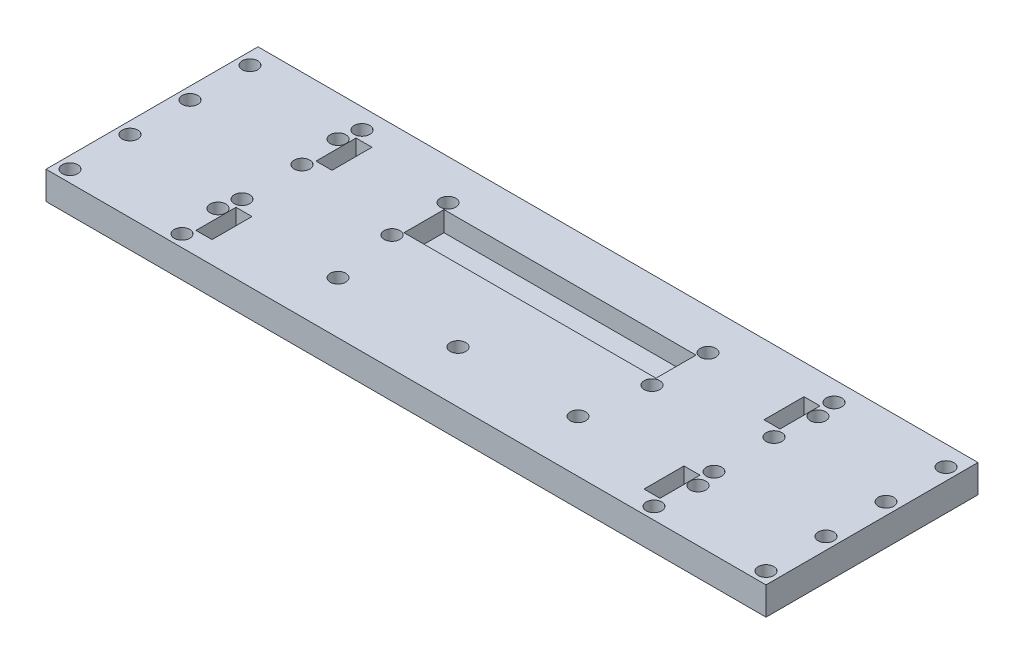
SolidWorks part; units mm, degrees
ref_plane "前视基准面" through (0, 0, 0) normal (0, 0, 1) x (1, 0, 0)
ref_plane "上视基准面" through (0, 0, 0) normal (0, 1, 0) x (1, 0, 0)
ref_plane "右视基准面" through (0, 0, 0) normal (1, 0, 0) x (0, 0, -1)
other "Configuration Table"
sketch "草图1" plane through (0, 0, 0) normal (0, 1, 0) x (1, 0, 0)
  line L0 (0, 20) -> (150, 20)
  line L1 (0, 0) -> (150, 0)
  line L2 (0, 0) -> (0, 30)
  line L3 (0, 30) -> (150, 30)
  line L4 (150, 0) -> (150, 30)
  line L6 (0, 30) -> (25, 30)
  line L7 (0, 30) -> (0, 60)
  line L8 (0, 60) -> (25, 60)
  line L9 (25, 30) -> (25, 60)
  line L10 (150, 30) -> (125, 30)
  line L11 (150, 30) -> (150, 60)
  line L12 (150, 60) -> (125, 60)
  line L13 (125, 30) -> (125, 60)
  line L14 (0, 0) -> (-15, 0)
  line L15 (0, 0) -> (0, 60)
  line L16 (0, 60) -> (-15, 60)
  line L17 (-15, 0) -> (-15, 60)
  line L18 (150, 60) -> (165, 60)
  line L19 (150, 60) -> (150, 0)
  line L20 (150, 0) -> (165, 0)
  line L21 (165, 60) -> (165, 0)
  circle A1 centre (15, 20) radius 1.95
  circle A2 centre (45, 20) radius 1.95
  circle A3 centre (75, 20) radius 1.95
  circle A4 centre (105, 20) radius 1.95
  circle A5 centre (135, 20) radius 1.95
  circle A6 centre (15, 50) radius 1.95
  circle A7 centre (135, 50) radius 1.95
  dimension "D5" = 15
  dimension "D6" = 30
  dimension "D7" = 3.9
  dimension "D12" = 3.9
  dimension "D14" = 15
  dimension "D15" = 15
  dimension "D16" = 3.9
  dimension "D17" = 30
  dimension "D1" = 30
  dimension "D2" = 150
  dimension "D3" = 10
  dimension "D8" = 40
  dimension "D9" = 25
  dimension "D10" = 25
  dimension "D11" = 30
  dimension "D13" = 30
  dimension "D18" = 15
  dimension "D19" = 15
  dimension "D4" = 5
extrude "凸台-拉伸1" add sketch "草图1" along normal blind 7 contours L3 L9 L8 L7 A6 | A5 L0 A4 A3 A2 A1 L2 L1 L4 | A5 L0 L4 L3 L2 A1 A2 A3 A4 | L13 L3 L11 L12 A7 | L15 L14 L17 L16 | L19 L18 L21 L20
sketch "草图2" plane through (0, 7, 0) normal (0, 1, 0) x (1, 0, 0)
  line L0 (-15, 0) -> (-15, 60) construction
  line L1 (-12, 55) -> (16, 55)
  line L2 (-12, 55) -> (-12, 40)
  line L3 (-12, 40) -> (16, 40)
  line L4 (16, 55) -> (16, 40)
  line L5 (-15, 60) -> (25, 60) construction
  line L6 (-12, 25) -> (-12, 10)
  line L7 (-12, 25) -> (16, 25)
  line L8 (16, 25) -> (16, 10)
  line L9 (-12, 10) -> (16, 10)
  line L10 (75, 0) -> (75, 91.2711)
  line L11 (-15, 0) -> (165, 0) construction
  line L12 (-12, 47.5) -> (19, 47.5)
  line L13 (-15, 32.5) -> (25, 32.5)
  line L14 (17, 42.5) -> (21, 42.5)
  line L15 (17, 42.5) -> (17, 52.5)
  line L16 (17, 52.5) -> (21, 52.5)
  line L17 (21, 42.5) -> (21, 52.5)
  line L18 (19, 52.5) -> (19, 42.5) construction
  line L19 (17, 47.5) -> (21, 47.5) construction
  line L20 (25, 30) -> (25, 60) construction
  line L21 (17, 12.5) -> (21, 12.5)
  line L22 (17, 22.5) -> (17, 12.5)
  line L23 (17, 22.5) -> (21, 22.5)
  line L24 (21, 22.5) -> (21, 12.5)
  line L25 (133, 22.5) -> (133, 12.5)
  line L26 (133, 22.5) -> (129, 22.5)
  line L27 (129, 22.5) -> (129, 12.5)
  line L28 (133, 12.5) -> (129, 12.5)
  line L29 (133, 42.5) -> (129, 42.5)
  line L30 (133, 42.5) -> (133, 52.5)
  line L31 (133, 52.5) -> (129, 52.5)
  line L32 (129, 42.5) -> (129, 52.5)
  circle A0 centre (-12, 55) radius 1.95
  circle A1 centre (16, 55) radius 1.95
  circle A2 centre (16, 40) radius 1.95
  circle A3 centre (16, 25) radius 1.95
  circle A4 centre (-12, 25) radius 1.95
  circle A5 centre (-12, 10) radius 1.95
  circle A6 centre (16, 10) radius 1.95
  circle A7 centre (-12, 40) radius 1.95
  circle A8 centre (162, 10) radius 1.95
  circle A9 centre (134, 10) radius 1.95
  circle A10 centre (134, 25) radius 1.95
  circle A11 centre (162, 25) radius 1.95
  circle A12 centre (134, 40) radius 1.95
  circle A13 centre (162, 40) radius 1.95
  circle A14 centre (134, 55) radius 1.95
  circle A15 centre (162, 55) radius 1.95
  point P49 (2, 40)
  dimension "D7" = 3.9
  dimension "D8" = 3.9
  dimension "D9" = 3.9
  dimension "D10" = 3.9
  dimension "D11" = 3.9
  dimension "D12" = 3.9
  dimension "D13" = 3.9
  dimension "D14" = 3.9
  dimension "D1" = 15
  dimension "D2" = 28
  dimension "D3" = 3
  dimension "D4" = 5
  dimension "D6" = 30
  dimension "D15" = 4
  dimension "D16" = 10
  dimension "D17" = 1
  dimension "D18" = 7.5
  dimension "D5" = 2
extrude "切除-拉伸1" cut sketch "草图2" against normal blind 6 contours L1 A0 L2 | L2 A0 L1 | L2 A7 L3 | L3 A7 L2 | L4 A2 L3 | L3 A2 L4 | L4 A1 L1 | L1 A1 L4 | L6 A5 L9 | L9 A5 L6 | L7 A4 L6 | L6 A4 L7 | L8 A3 L7 | L7 A3 L8 | L8 A6 L9 | L9 A6 L8 | A9 | A8 | A11 | A10 | A12 | A14 | A15 | A13
sketch "草图4" plane through (0, 7, 0) normal (0, 1, 0) x (1, 0, 0)
  line L0 (75, 0) -> (75, 91.2711) construction
  line L1 (-15, 32.5) -> (25, 32.5) construction
  line L2 (-12, 47.5) -> (19, 47.5) construction
  line L3 (75, 0) -> (75, 91.2711)
  line L4 (-12, 25) -> (-12, 10)
  line L5 (-12, 10) -> (16, 10)
  line L6 (16, 10) -> (16, 25)
  line L7 (16, 25) -> (-12, 25)
  line L8 (-12, 25) -> (-12, 10)
  line L9 (-12, 10) -> (16, 10)
  line L10 (16, 10) -> (16, 25)
  line L11 (16, 25) -> (-12, 25)
  line L12 (16, 55) -> (-12, 55)
  line L13 (16, 40) -> (16, 55)
  line L14 (-12, 40) -> (16, 40)
  line L15 (-12, 55) -> (-12, 40)
  line L16 (16, 55) -> (-12, 55)
  line L17 (16, 40) -> (16, 55)
  line L18 (-12, 40) -> (16, 40)
  line L19 (-12, 55) -> (-12, 40)
  line L20 (129, 42.5) -> (133, 42.5)
  line L21 (129, 52.5) -> (129, 42.5)
  line L22 (133, 52.5) -> (129, 52.5)
  line L23 (133, 42.5) -> (133, 52.5)
  line L24 (129, 42.5) -> (133, 42.5)
  line L25 (129, 52.5) -> (129, 42.5)
  line L26 (133, 52.5) -> (129, 52.5)
  line L27 (133, 42.5) -> (133, 52.5)
  line L28 (133, 12.5) -> (133, 22.5)
  line L29 (129, 12.5) -> (133, 12.5)
  line L30 (129, 22.5) -> (129, 12.5)
  line L31 (133, 22.5) -> (129, 22.5)
  line L32 (133, 12.5) -> (133, 22.5)
  line L33 (129, 12.5) -> (133, 12.5)
  line L34 (129, 22.5) -> (129, 12.5)
  line L35 (133, 22.5) -> (129, 22.5)
  line L36 (17, 12.5) -> (21, 12.5)
  line L37 (21, 12.5) -> (21, 22.5)
  line L38 (21, 22.5) -> (17, 22.5)
  line L39 (17, 22.5) -> (17, 12.5)
  line L40 (17, 12.5) -> (21, 12.5)
  line L41 (21, 12.5) -> (21, 22.5)
  line L42 (21, 22.5) -> (17, 22.5)
  line L43 (17, 22.5) -> (17, 12.5)
  line L44 (17, 42.5) -> (21, 42.5)
  line L45 (17, 52.5) -> (17, 42.5)
  line L46 (21, 52.5) -> (17, 52.5)
  line L47 (21, 42.5) -> (21, 52.5)
  line L48 (17, 42.5) -> (21, 42.5)
  line L49 (17, 52.5) -> (17, 42.5)
  line L50 (21, 52.5) -> (17, 52.5)
  line L51 (21, 42.5) -> (21, 52.5)
  line L52 (-15, 32.5) -> (25, 32.5)
  line L53 (-12, 47.5) -> (19, 47.5)
  circle A1 centre (16, 25) radius 1.95
  circle A2 centre (16, 25) radius 1.95
  circle A3 centre (16, 40) radius 1.95
  circle A4 centre (16, 40) radius 1.95
  circle A5 centre (16, 55) radius 1.95
  circle A6 centre (16, 55) radius 1.95
  circle A7 centre (-12, 55) radius 1.95
  circle A8 centre (-12, 55) radius 1.95
  circle A9 centre (162, 25) radius 1.95
  circle A10 centre (162, 25) radius 1.95
  circle A11 centre (134, 25) radius 1.95
  circle A12 centre (134, 25) radius 1.95
  circle A13 centre (134, 10) radius 1.95
  circle A14 centre (134, 10) radius 1.95
  circle A15 centre (162, 10) radius 1.95
  circle A16 centre (162, 10) radius 1.95
  circle A17 centre (-12, 40) radius 1.95
  circle A18 centre (-12, 40) radius 1.95
  circle A19 centre (16, 10) radius 1.95
  circle A20 centre (16, 10) radius 1.95
  circle A21 centre (-12, 10) radius 1.95
  circle A22 centre (-12, 10) radius 1.95
  circle A23 centre (-12, 25) radius 1.95
  circle A24 centre (-12, 25) radius 1.95
  circle A25 centre (162, 55) radius 1.95
  circle A26 centre (162, 55) radius 1.95
  circle A27 centre (134, 55) radius 1.95
  circle A28 centre (134, 55) radius 1.95
  circle A29 centre (162, 40) radius 1.95
  circle A30 centre (162, 40) radius 1.95
  circle A31 centre (134, 40) radius 1.95
  circle A32 centre (134, 40) radius 1.95
  dimension "D1" = 0
  dimension "D2" = 0
  dimension "D3" = 0
  dimension "D4" = 0
  dimension "D5" = 0
  dimension "D6" = 0
  dimension "D7" = 0
  dimension "D8" = 0
  dimension "D9" = 0
  dimension "D10" = 0
  dimension "D11" = 0
  dimension "D12" = 0
  dimension "D13" = 0
  dimension "D14" = 0
  dimension "D15" = 0
  dimension "D16" = 0
  dimension "D17" = 0
  dimension "D18" = 0
  dimension "D19" = 0
  dimension "D20" = 0
  dimension "D21" = 0
  dimension "D22" = 0
extrude "切除-拉伸2" cut sketch "草图4" against normal blind 5
sketch "草图5" plane through (0, 7, 0) normal (0, 1, 0) x (1, 0, 0)
  line L1 (-15, 0) -> (165, 0)
  line L2 (-15, 0) -> (-15, 7)
  line L3 (-15, 7) -> (165, 7)
  line L4 (165, 0) -> (165, 7)
  line L8 (-15, 0) -> (165, 0)
  line L9 (165, 0) -> (165, 60)
  line L10 (165, 60) -> (125, 60)
  line L11 (125, 60) -> (125, 30)
  line L12 (125, 30) -> (25, 30)
  line L13 (25, 30) -> (25, 60)
  line L14 (25, 60) -> (-15, 60)
  line L15 (-15, 60) -> (-15, 0)
  line L16 (-15, 0) -> (165, 0)
  line L17 (165, 0) -> (165, 60)
  line L18 (165, 60) -> (125, 60)
  line L19 (125, 60) -> (125, 30)
  line L20 (125, 30) -> (25, 30)
  line L21 (25, 30) -> (25, 60)
  line L22 (25, 60) -> (-15, 60)
  line L23 (-15, 60) -> (-15, 0)
  line M32 (-15, 0) -> (165, 0)
  line M33 (165, 0) -> (165, 60)
  line M39 (-15, 60) -> (-15, 0)
  dimension "D2" = 7
  dimension "D1" = 0
extrude "切除-拉伸3" cut sketch "草图5" against normal blind 10 contours L3 M39 M32 M33
sketch "草图6" plane through (0, 0, -30) normal (0, 0, -1) x (-1, 0, 0)
  line L4 (-125, 0) -> (-25, 0)
  line L5 (-25, 0) -> (-25, 7)
  line L6 (-25, 7) -> (-125, 7)
  line L7 (-125, 7) -> (-125, 0)
  line L8 (-125, 0) -> (-25, 0)
  line L9 (-25, 0) -> (-25, 7)
  line L10 (-25, 7) -> (-125, 7)
  line L11 (-125, 7) -> (-125, 0)
  dimension "D1" = 0
extrude "凸台-拉伸2" add sketch "草图6" along normal through all
sketch "草图7" plane through (0, 7, 0) normal (0, 1, 0) x (1, 0, 0)
  line L0 (75, 7) -> (75, 60)
  line L1 (-15, 7) -> (165, 7) construction
  line L2 (165, 60) -> (-15, 60) construction
  line L4 (42.5, 36) -> (107.5, 36)
  line L5 (42.5, 36) -> (42.5, 50)
  line L6 (42.5, 50) -> (107.5, 50)
  line L7 (107.5, 36) -> (107.5, 50)
  line L8 (75, 50) -> (75, 36) construction
  line L9 (42.5, 43) -> (107.5, 43) construction
  circle A0 centre (42.5, 50) radius 1.95
  circle A1 centre (42.5, 36) radius 1.95
  circle A2 centre (107.5, 36) radius 1.95
  circle A3 centre (107.5, 50) radius 1.95
  point P6 (75, 43)
  dimension "D4" = 3.9
  dimension "D5" = 3.9
  dimension "D6" = 3.9
  dimension "D7" = 3.9
  dimension "D1" = 14
  dimension "D2" = 65
  dimension "D3" = 10
extrude "切除-拉伸4" cut sketch "草图7" against normal blind 5 contours L5 A0 L6 | L6 A0 L5 | L5 A1 L4 | L4 A1 L5 | L4 A2 L7 | L7 A2 L4 | L6 A3 L7 | L7 A3 L6
sketch "草图8" plane through (0, 7, 0) normal (0, 1, 0) x (1, 0, 0)
  line L0 (75, 7) -> (75, 60) construction
  line L1 (75, 7) -> (75, 60)
  line L2 (42.5, 36) -> (107.5, 50)
  line L4 (42.5, 36) -> (107.5, 36)
  line L5 (107.5, 36) -> (107.5, 50)
  line L6 (107.5, 50) -> (42.5, 50)
  line L7 (42.5, 50) -> (42.5, 36)
  line L8 (42.5, 36) -> (107.5, 36)
  line L9 (107.5, 36) -> (107.5, 50)
  line L10 (107.5, 50) -> (42.5, 50)
  line L11 (42.5, 50) -> (42.5, 36)
  line L12 (43.5, 38) -> (106.5, 38)
  line L13 (43.5, 38) -> (43.5, 48)
  line L14 (43.5, 48) -> (106.5, 48)
  line L15 (106.5, 38) -> (106.5, 48)
  line L16 (75, 48) -> (75, 38) construction
  line L17 (43.5, 43) -> (106.5, 43) construction
  circle A1 centre (107.5, 50) radius 1.95
  circle A2 centre (107.5, 50) radius 1.95
  circle A3 centre (107.5, 36) radius 1.95
  circle A4 centre (107.5, 36) radius 1.95
  circle A5 centre (42.5, 36) radius 1.95
  circle A6 centre (42.5, 36) radius 1.95
  circle A7 centre (42.5, 50) radius 1.95
  circle A8 centre (42.5, 50) radius 1.95
  point P18 (75, 43)
  point P21 (75, 43)
  dimension "D6" = 63
  dimension "D7" = 10
  dimension "D1" = 0
  dimension "D2" = 0
  dimension "D3" = 0
  dimension "D4" = 0
  dimension "D5" = 0
extrude "切除-拉伸5" cut sketch "草图8" against normal blind 5 contours L12 L15 L14 L2 L1 | L14 L1 L2 | L14 L13 L12 L2 L1 | L2 L12 L1
